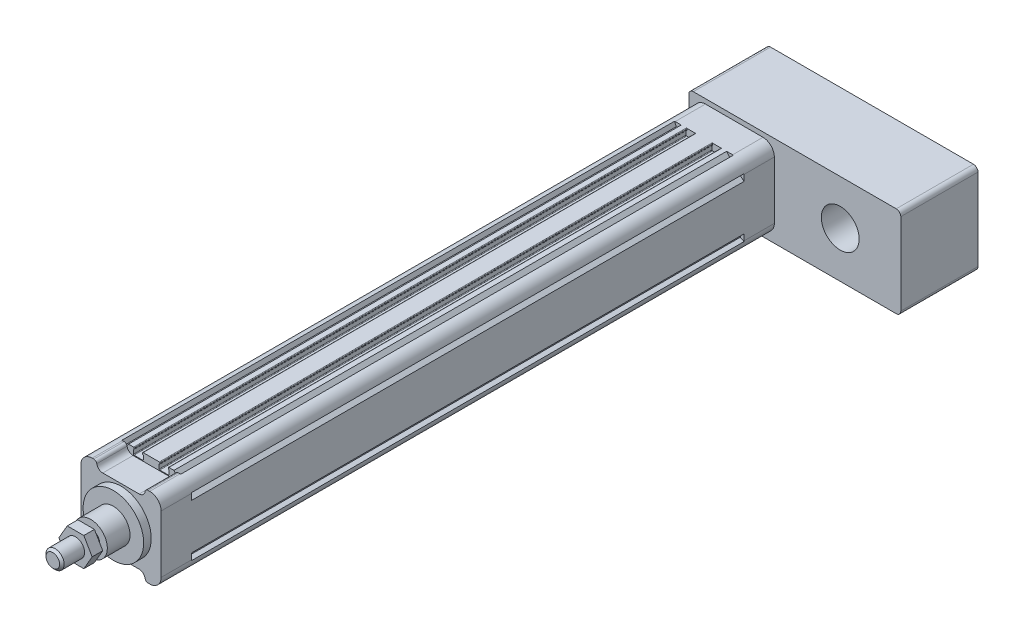
SolidWorks part; units mm, degrees
ref_plane "Front" through (0, 0, 0) normal (0, 0, 1) x (1, 0, 0)
ref_plane "Top" through (0, 0, 0) normal (0, 1, 0) x (1, 0, 0)
ref_plane "Right" through (0, 0, 0) normal (1, 0, 0) x (0, 0, -1)
sketch "草图1" plane through (0, 0, 0) normal (0, 0, 1) x (1, 0, 0)
  line L0 (19.7737, 3) -> (23.3, 3)
  line L1 (23.3, 3) -> (23.3, -3)
  line L2 (23.3, -3) -> (19.7737, -3)
  line L3 (-19.7737, -3) -> (-23.3, -3)
  line L4 (-23.3, -3) -> (-23.3, 3)
  line L5 (-23.3, 3) -> (-19.7737, 3)
  line L6 (-18.2, 24) -> (-19.4434, 26.4869)
  line L7 (-26.4869, 19.4434) -> (-24, 18.2)
  line L8 (-24, 18.2) -> (-24, 17.1)
  line L9 (-24, 17.1) -> (-26.5, 15)
  line L10 (-26.5, 15) -> (-26.5, -15)
  line L11 (-26.5, -15) -> (-24, -17.1)
  line L12 (-24, -17.1) -> (-24, -18.2)
  line L13 (-24, -18.2) -> (-26.4869, -19.4434)
  line L14 (-19.4434, -26.4869) -> (-18.2, -24)
  line L15 (-18.2, -24) -> (-17.1, -24)
  line L16 (-17.1, -24) -> (-15, -26.5)
  line L17 (-15, -26.5) -> (-11.65, -26.5)
  line L18 (-11.25, -26.1) -> (-11.25, -25.6)
  line L19 (-11.65, -25.2) -> (-11.75, -25.2)
  line L20 (-11.75, -25.2) -> (-11.75, -22.4)
  line L21 (-11.35, -22) -> (-5.65, -22)
  line L22 (-5.25, -22.4) -> (-5.25, -25.2)
  line L23 (-5.25, -25.2) -> (-5.35, -25.2)
  line L24 (-5.75, -25.6) -> (-5.75, -26.1)
  line L25 (-5.35, -26.5) -> (5.35, -26.5)
  line L26 (5.75, -26.1) -> (5.75, -25.6)
  line L27 (5.35, -25.2) -> (5.25, -25.2)
  line L28 (5.25, -25.2) -> (5.25, -22.4)
  line L29 (5.65, -22) -> (11.35, -22)
  line L30 (11.75, -22.4) -> (11.75, -25.2)
  line L31 (11.75, -25.2) -> (11.65, -25.2)
  line L32 (11.25, -25.6) -> (11.25, -26.1)
  line L33 (11.65, -26.5) -> (15, -26.5)
  line L34 (15, -26.5) -> (17.1, -24)
  line L35 (17.1, -24) -> (18.2, -24)
  line L36 (18.2, -24) -> (19.4434, -26.4869)
  line L37 (26.4869, -19.4434) -> (24, -18.2)
  line L38 (24, -18.2) -> (24, -17.1)
  line L39 (24, -17.1) -> (26.5, -15)
  line L40 (26.5, -15) -> (26.5, 15)
  line L41 (26.5, 15) -> (24, 17.1)
  line L42 (24, 17.1) -> (24, 18.2)
  line L43 (24, 18.2) -> (26.4869, 19.4434)
  line L44 (19.4434, 26.4869) -> (18.2, 24)
  line L45 (18.2, 24) -> (17.1, 24)
  line L46 (17.1, 24) -> (15, 26.5)
  line L47 (15, 26.5) -> (11.65, 26.5)
  line L48 (11.25, 26.1) -> (11.25, 25.6)
  line L49 (11.65, 25.2) -> (11.75, 25.2)
  line L50 (11.75, 25.2) -> (11.75, 22.4)
  line L51 (11.35, 22) -> (5.65, 22)
  line L52 (5.25, 22.4) -> (5.25, 25.2)
  line L53 (5.25, 25.2) -> (5.35, 25.2)
  line L54 (5.75, 25.6) -> (5.75, 26.1)
  line L55 (5.35, 26.5) -> (-5.35, 26.5)
  line L56 (-5.75, 26.1) -> (-5.75, 25.6)
  line L57 (-5.35, 25.2) -> (-5.25, 25.2)
  line L58 (-5.25, 25.2) -> (-5.25, 22.4)
  line L59 (-5.65, 22) -> (-11.35, 22)
  line L60 (-11.75, 22.4) -> (-11.75, 25.2)
  line L61 (-11.75, 25.2) -> (-11.65, 25.2)
  line L62 (-11.25, 25.6) -> (-11.25, 26.1)
  line L63 (-11.65, 26.5) -> (-15, 26.5)
  line L64 (-15, 26.5) -> (-17.1, 24)
  line L65 (-17.1, 24) -> (-18.2, 24)
  arc A0 (19.7737, 3) -> (-19.7737, 3) centre (0, 0) ccw
  arc A1 (-19.7737, -3) -> (19.7737, -3) centre (0, 0) ccw
  circle A2 centre (19, 19) radius 2.1
  circle A3 centre (19, -19) radius 2.1
  circle A4 centre (-19, -19) radius 2.1
  circle A5 centre (-19, 19) radius 2.1
  arc A6 (-19.4434, 26.4869) -> (-26.4869, 19.4434) centre (-19, 19) ccw
  arc A7 (-26.4869, -19.4434) -> (-19.4434, -26.4869) centre (-19, -19) ccw
  arc A8 (-11.65, -26.5) -> (-11.25, -26.1) centre (-11.65, -26.1) ccw
  arc A9 (-11.25, -25.6) -> (-11.65, -25.2) centre (-11.65, -25.6) ccw
  arc A10 (-11.35, -22) -> (-11.75, -22.4) centre (-11.35, -22.4) ccw
  arc A11 (-5.25, -22.4) -> (-5.65, -22) centre (-5.65, -22.4) ccw
  arc A12 (-5.35, -25.2) -> (-5.75, -25.6) centre (-5.35, -25.6) ccw
  arc A13 (-5.75, -26.1) -> (-5.35, -26.5) centre (-5.35, -26.1) ccw
  arc A14 (5.35, -26.5) -> (5.75, -26.1) centre (5.35, -26.1) ccw
  arc A15 (5.75, -25.6) -> (5.35, -25.2) centre (5.35, -25.6) ccw
  arc A16 (5.65, -22) -> (5.25, -22.4) centre (5.65, -22.4) ccw
  arc A17 (11.75, -22.4) -> (11.35, -22) centre (11.35, -22.4) ccw
  arc A18 (11.65, -25.2) -> (11.25, -25.6) centre (11.65, -25.6) ccw
  arc A19 (11.25, -26.1) -> (11.65, -26.5) centre (11.65, -26.1) ccw
  arc A20 (19.4434, -26.4869) -> (26.4869, -19.4434) centre (19, -19) ccw
  arc A21 (26.4869, 19.4434) -> (19.4434, 26.4869) centre (19, 19) ccw
  arc A22 (11.65, 26.5) -> (11.25, 26.1) centre (11.65, 26.1) ccw
  arc A23 (11.25, 25.6) -> (11.65, 25.2) centre (11.65, 25.6) ccw
  arc A24 (11.35, 22) -> (11.75, 22.4) centre (11.35, 22.4) ccw
  arc A25 (5.25, 22.4) -> (5.65, 22) centre (5.65, 22.4) ccw
  arc A26 (5.35, 25.2) -> (5.75, 25.6) centre (5.35, 25.6) ccw
  arc A27 (5.75, 26.1) -> (5.35, 26.5) centre (5.35, 26.1) ccw
  arc A28 (-5.35, 26.5) -> (-5.75, 26.1) centre (-5.35, 26.1) ccw
  arc A29 (-5.75, 25.6) -> (-5.35, 25.2) centre (-5.35, 25.6) ccw
  arc A30 (-5.65, 22) -> (-5.25, 22.4) centre (-5.65, 22.4) ccw
  arc A31 (-11.75, 22.4) -> (-11.35, 22) centre (-11.35, 22.4) ccw
  arc A32 (-11.65, 25.2) -> (-11.25, 25.6) centre (-11.65, 25.6) ccw
  arc A33 (-11.25, 26.1) -> (-11.65, 26.5) centre (-11.65, 26.1) ccw
extrude "凸台-拉伸1" add sketch "草图1" along normal blind 365
sketch "草图6" plane through (0, 0, 365) normal (0, 0, 1) x (1, 0, 0)
  line L0 (0, 0) -> (19, 0) construction
  line L2 (-26.5, -19) -> (-26.5, 19)
  line L3 (-19, 26.5) -> (-17.9161, 26.5)
  line L4 (26.5, -19) -> (26.5, 19)
  line L5 (-26.5, -26.5) -> (26.5, 26.5) construction
  line L6 (-26.5, 26.5) -> (26.5, -26.5) construction
  line L7 (-12, 21.5) -> (12, 21.5)
  line L9 (19, 26.5) -> (17.9161, 26.5)
  line L10 (19, -26.5) -> (17.9161, -26.5)
  line L11 (-12, -21.5) -> (12, -21.5)
  line L12 (-19, -26.5) -> (-17.9161, -26.5)
  arc A0 (12, 21.5) -> (15.9441, 24.8333) centre (12, 25.5) ccw
  arc A1 (-15.9441, 24.8333) -> (-12, 21.5) centre (-12, 25.5) ccw
  arc A2 (-15.9441, 24.8333) -> (-17.9161, 26.5) centre (-17.9161, 24.5) ccw
  arc A3 (15.9441, 24.8333) -> (17.9161, 26.5) centre (17.9161, 24.5) cw
  arc A4 (-26.5, -19) -> (-19, -26.5) centre (-19, -19) ccw
  arc A5 (19, -26.5) -> (26.5, -19) centre (19, -19) ccw
  arc A6 (26.5, 19) -> (19, 26.5) centre (19, 19) ccw
  arc A7 (-26.5, 19) -> (-19, 26.5) centre (-19, 19) cw
  arc A8 (15.9441, -24.8333) -> (17.9161, -26.5) centre (17.9161, -24.5) ccw
  arc A9 (12, -21.5) -> (15.9441, -24.8333) centre (12, -25.5) cw
  arc A10 (-15.9441, -24.8333) -> (-12, -21.5) centre (-12, -25.5) cw
  arc A11 (-15.9441, -24.8333) -> (-17.9161, -26.5) centre (-17.9161, -24.5) cw
  point P0 (0, 0)
  point P9 (0, 21.5)
  point P13 (20, 20.8461)
  point P16 (-12, 20.8461)
  dimension "D5" = 4
  dimension "D6" = 2
  dimension "D7" = 2
  dimension "D9" = 7.5
  dimension "D1" = 53
  dimension "D2" = 53
  dimension "D3" = 26.5
  dimension "D4" = 24
  dimension "D8" = 5
extrude "凸台-拉伸2" add sketch "草图6" along normal blind 20
sketch "草图7" plane through (0, 0, 385) normal (0, 0, 1) x (1, 0, 0)
  circle A0 centre (0, 0) radius 20
  dimension "D1" = 40
extrude "凸台-拉伸3" add sketch "草图7" along normal blind 5
sketch "草图9" plane through (0, 0, 390) normal (0, 0, 1) x (1, 0, 0)
  circle A0 centre (0, 0) radius 11
  dimension "D1" = 22
extrude "凸台-拉伸4" add sketch "草图9" along normal blind 15
sketch "草图10" plane through (0, 0, 405) normal (0, 0, 1) x (1, 0, 0)
  circle A0 centre (0, 0) radius 6
  dimension "D1" = 12
extrude "凸台-拉伸5" add sketch "草图10" along normal blind 25
sketch "草图11" plane through (0, 0, 0) normal (0, 0, -1) x (-1, 0, 0)
  line L1 (-19, -26.5) -> (19, -26.5)
  line L2 (-26.5, -19) -> (-26.5, 19)
  line L3 (-19, 26.5) -> (19, 26.5)
  line L4 (26.5, -19) -> (26.5, 19)
  line L5 (-26.5, -26.5) -> (26.5, 26.5) construction
  line L6 (-26.5, 26.5) -> (26.5, -26.5) construction
  arc A0 (-26.5, -19) -> (-19, -26.5) centre (-19, -19) ccw
  arc A1 (19, -26.5) -> (26.5, -19) centre (19, -19) ccw
  arc A2 (26.5, 19) -> (19, 26.5) centre (19, 19) ccw
  arc A3 (-26.5, 19) -> (-19, 26.5) centre (-19, 19) cw
  point P0 (0, 0)
  dimension "D3" = 7.5
  dimension "D1" = 53
  dimension "D2" = 53
extrude "凸台-拉伸6" add sketch "草图11" along normal blind 20
sketch "草图12" plane through (0, 0, -20) normal (0, 0, -1) x (-1, 0, 0)
  line L1 (-107, -30.4042) -> (27, -30.4042)
  line L2 (-110, -27.4042) -> (-110, 26.5958)
  line L3 (-107, 29.5958) -> (27, 29.5958)
  line L4 (30, -27.4042) -> (30, 26.5958)
  line L5 (-110, -30.4042) -> (30, 29.5958) construction
  line L6 (-110, 29.5958) -> (30, -30.4042) construction
  arc A0 (27, 29.5958) -> (30, 26.5958) centre (27, 26.5958) cw
  arc A1 (30, -27.4042) -> (27, -30.4042) centre (27, -27.4042) cw
  arc A2 (-110, -27.4042) -> (-107, -30.4042) centre (-107, -27.4042) ccw
  arc A3 (-110, 26.5958) -> (-107, 29.5958) centre (-107, 26.5958) cw
  point P0 (-40, -0.4042)
  dimension "D4" = 3
  dimension "D1" = 60
  dimension "D2" = 140
  dimension "D3" = 30
extrude "凸台-拉伸7" add sketch "草图12" along normal blind 51
sketch "草图13" plane through (0, 0, -20) normal (0, 0, 1) x (1, 0, 0)
  circle A0 centre (70, 0) radius 12.5
  dimension "D2" = 25
  dimension "D1" = 70
extrude "切除-拉伸2" cut sketch "草图13" against normal blind 30
hole_wizard "M6 螺纹孔1" positions "草图14" profile "草图15" tap size "M6" standard "GB"
sketch "草图14" plane through (0, 0, -71) normal (0, 0, -1) x (-1, 0, 0)
  line L0 (30, -27.4042) -> (30, 26.5958) construction
  point P0 (19, -19)
  dimension "D1" = 11
  dimension "D2" = 19
sketch "草图15" plane through (-19, -19, -71) normal (1, 0, 0) x (0, 1, 0)
  line L0 (0, 0) -> (0, 16.5022)
  line L1 (0, 16.5022) -> (2.5, 15)
  line L2 (2.5, 15) -> (2.5, 0)
  line L5 (2.5, 0) -> (0, 0)
  line L10 (0, 16.5022) -> (-2.5, 15) construction
  line L11 (0, -6.35) -> (0, 107.95) construction
  dimension "螺纹孔钻头直径" = 5
  dimension "螺纹孔钻头深度" = 15
  dimension "导头角度" = 118
cosmetic thread "孔螺蚊线4" parameters "D1"=12, "D2"=6
pattern_linear "阵列(线性)1" count 2 spacing 38 along (0, 1, 0) count 2 spacing 38 along (1, 0, 0) of "M6 螺纹孔1"
hole_wizard "M6 螺纹孔2" positions "草图16" profile "草图17" tap size "M6" standard "GB"
sketch "草图16" plane through (0, 0, -71) normal (0, 0, -1) x (-1, 0, 0)
  circle A1 centre (-19, 19) radius 2.5 construction
  circle A2 centre (-19, -19) radius 2.5 construction
  point P0 (-84, -19)
  point P2 (-84, 19)
  dimension "D3" = 65
  dimension "D1" = 19
  dimension "D2" = 19
  dimension "D4" = 65
sketch "草图17" plane through (84, -19, -71) normal (1, 0, 0) x (0, 1, 0)
  line L0 (0, 0) -> (0, 16.5022)
  line L1 (0, 16.5022) -> (2.5, 15)
  line L2 (2.5, 15) -> (2.5, 0)
  line L5 (2.5, 0) -> (0, 0)
  line L10 (0, 16.5022) -> (-2.5, 15) construction
  line L11 (0, -6.35) -> (0, 107.95) construction
  dimension "螺纹孔钻头直径" = 5
  dimension "螺纹孔钻头深度" = 15
  dimension "导头角度" = 118
cosmetic thread "孔螺蚊线5" parameters "D1"=12, "D2"=6
cosmetic thread "孔螺蚊线6" parameters "D1"=12, "D2"=6
hole_wizard "M6 螺纹孔3" positions "草图19" profile "草图20" tap size "M6" standard "GB"
sketch "草图19" plane through (-26.5, 0, 0) normal (-1, 0, 0) x (0, 0, 1)
  line L0 (385, 19) -> (385, -19) construction
  point P0 (375, 11)
  point P2 (375, -11)
  dimension "D1" = 10
  dimension "D2" = 10
  dimension "D3" = 22
  dimension "D4" = 11
sketch "草图20" plane through (-26.5, 11, 375) normal (0, 1, 0) x (0, 0, 1)
  line L0 (0, 0) -> (0, 16.5022)
  line L1 (0, 16.5022) -> (2.5, 15)
  line L2 (2.5, 15) -> (2.5, 0)
  line L5 (2.5, 0) -> (0, 0)
  line L10 (0, 16.5022) -> (-2.5, 15) construction
  line L11 (0, -6.35) -> (0, 107.95) construction
  dimension "螺纹孔钻头直径" = 5
  dimension "螺纹孔钻头深度" = 15
  dimension "导头角度" = 118
cosmetic thread "孔螺蚊线7" parameters "D1"=12, "D2"=6
cosmetic thread "孔螺蚊线8" parameters "D1"=12, "D2"=6
hole_wizard "M6 螺纹孔4" positions "草图21" profile "草图22" tap size "M6" standard "GB"
sketch "草图21" plane through (-26.5, 0, 0) normal (-1, 0, 0) x (0, 0, 1)
  line L0 (-20, -27.4042) -> (-20, 26.5958) construction
  line L1 (-20, -19) -> (-20, 19) construction
  point P0 (-10, 11)
  point P2 (-10, -11)
  dimension "D1" = 10
  dimension "D2" = 10
  dimension "D3" = 11
  dimension "D4" = 11
sketch "草图22" plane through (-26.5, 11, -10) normal (0, 1, 0) x (0, 0, 1)
  line L0 (0, 0) -> (0, 16.5022)
  line L1 (0, 16.5022) -> (2.5, 15)
  line L2 (2.5, 15) -> (2.5, 0)
  line L5 (2.5, 0) -> (0, 0)
  line L10 (0, 16.5022) -> (-2.5, 15) construction
  line L11 (0, -6.35) -> (0, 107.95) construction
  dimension "螺纹孔钻头直径" = 5
  dimension "螺纹孔钻头深度" = 15
  dimension "导头角度" = 118
cosmetic thread "孔螺蚊线9" parameters "D1"=12, "D2"=6
cosmetic thread "孔螺蚊线10" parameters "D1"=12, "D2"=6
chamfer "倒角1" distance 1.5 angle 45 1 edges at (6, 0, 430)
sketch "草图23" plane through (0, 0, 405) normal (0, 0, 1) x (1, 0, 0)
  line L1 (10.9697, 0) -> (5.4848, 9.5)
  line L2 (5.4848, 9.5) -> (-5.4848, 9.5)
  line L3 (-5.4848, 9.5) -> (-10.9697, 0)
  line L4 (-10.9697, 0) -> (-5.4848, -9.5)
  line L5 (-5.4848, -9.5) -> (5.4848, -9.5)
  line L6 (5.4848, -9.5) -> (10.9697, 0)
  circle A0 centre (0, 0) radius 9.5 construction
  dimension "D1" = 19
extrude "凸台-拉伸8" add sketch "草图23" along normal blind 7 from offset 3
